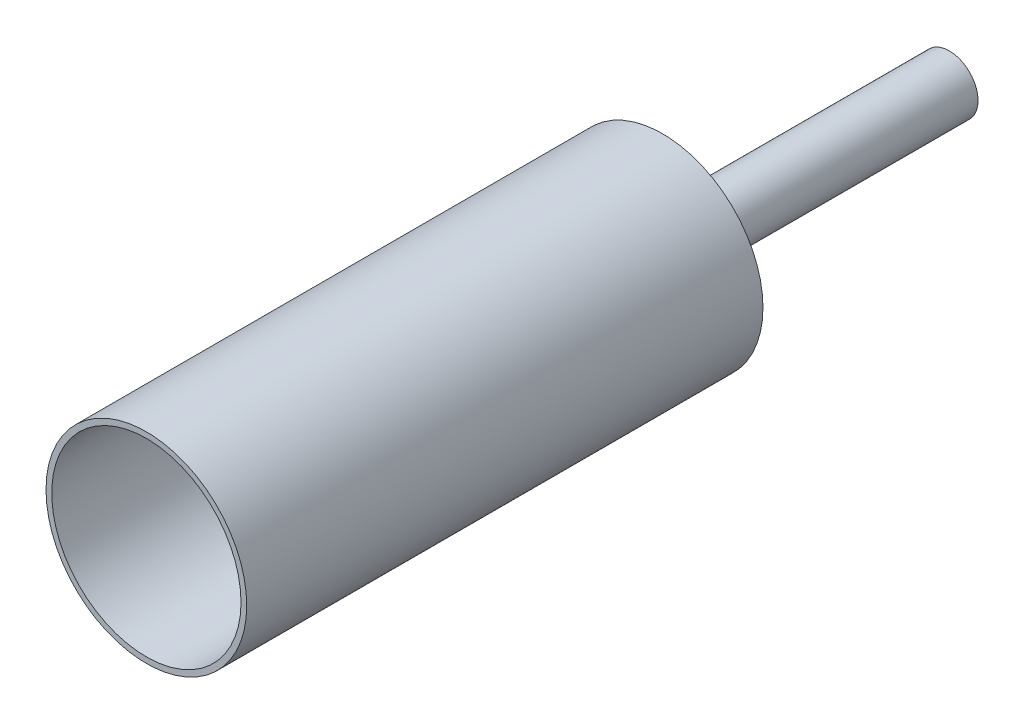
SolidWorks part; units mm, degrees
ref_plane "Piano frontale" through (0, 0, 0) normal (0, 0, 1) x (1, 0, 0)
ref_plane "Piano superiore" through (0, 0, 0) normal (0, 1, 0) x (1, 0, 0)
ref_plane "Piano destro" through (0, 0, 0) normal (1, 0, 0) x (0, 0, -1)
sketch "Schizzo1" plane through (0, 0, 0) normal (0, 0, 1) x (1, 0, 0)
  circle A0 centre (0, 0) radius 17.5
  dimension "D1" = 35
extrude "Estrusione-Estrusione1" add sketch "Schizzo1" along normal blind 90
sketch "Schizzo2" plane through (0, 0, 90) normal (0, 0, 1) x (1, 0, 0)
  circle A0 centre (0, 0) radius 16.5
  dimension "D1" = 33
extrude "Taglio-Estrusione1" cut sketch "Schizzo2" against normal blind 88 contours A0
sketch "Schizzo3" plane through (0, 0, 0) normal (0, 0, -1) x (-1, 0, 0)
  circle A0 centre (0, 0) radius 5
  dimension "D1" = 10
extrude "Estrusione-Estrusione2" add sketch "Schizzo3" along normal blind 50
